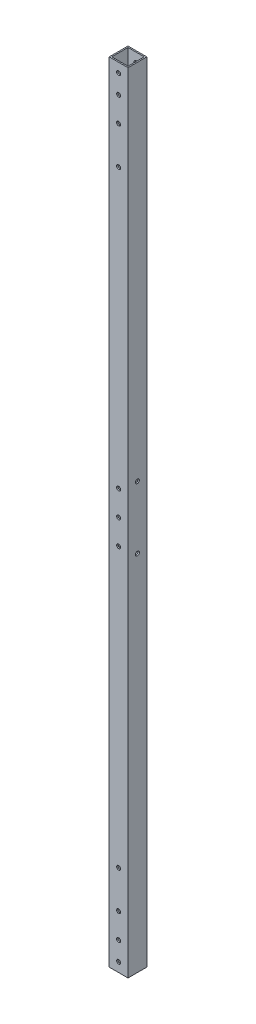
SolidWorks part; units mm, degrees
ref_plane "前视基准面" through (0, 0, 0) normal (0, 0, 1) x (1, 0, 0)
ref_plane "上视基准面" through (0, 0, 0) normal (0, 1, 0) x (1, 0, 0)
ref_plane "右视基准面" through (0, 0, 0) normal (1, 0, 0) x (0, 0, -1)
sketch "草图2" plane through (0, 0, 0) normal (0, 1, 0) x (1, 0, 0)
  line L1 (-7.5, -7.5) -> (7.5, -7.5)
  line L2 (-7.5, -7.5) -> (-7.5, 7.5)
  line L3 (-7.5, 7.5) -> (7.5, 7.5)
  line L4 (7.5, -7.5) -> (7.5, 7.5)
  line L5 (-7.5, -7.5) -> (7.5, 7.5) construction
  line L6 (-7.5, 7.5) -> (7.5, -7.5) construction
  point P0 (0, 0)
  dimension "D1" = 15
  dimension "D2" = 15
extrude "拉伸-薄壁1" add sketch "草图2" along normal blind 630 thin thin type one direction reverse wall 1
sketch "草图3" plane through (0, 0, 7.5) normal (0, 0, 1) x (1, 0, 0)
  line L0 (0, 0) -> (0, 630) construction
  line L1 (-7.5, 630) -> (7.5, 630) construction
  line L2 (-1000, 315) -> (49000, 315) construction
  line L3 (-7.5, 0) -> (7.5, 0) construction
  circle A0 centre (0, 7.5) radius 1.6
  circle A1 centre (0, 22.5) radius 1.6
  circle A2 centre (0, 42.5) radius 1.6
  circle A3 centre (0, 72.5) radius 1.6
  circle A4 centre (0, 315) radius 1.6
  circle A5 centre (0, 295) radius 1.6
  circle A6 centre (0, 335) radius 1.6
  circle A7 centre (0, 557.5) radius 1.6
  circle A8 centre (0, 587.5) radius 1.6
  circle A9 centre (0, 607.5) radius 1.6
  circle A10 centre (0, 622.5) radius 1.6
  point P14 (0, 315)
  dimension "D1" = 3.2
  dimension "D3" = 15
  dimension "D4" = 20
  dimension "D5" = 30
  dimension "D6" = 20
  dimension "D7" = 20
  dimension "D2" = 7.5
extrude "切除-拉伸1" cut sketch "草图3" against normal through all
sketch "草图4" plane through (7.5, 0, 0) normal (1, 0, 0) x (0, 0, -1)
  line L0 (0, 0) -> (0, 630) construction
  line L1 (-7.5, 630) -> (7.5, 630) construction
  circle A0 centre (0, 290) radius 1.6
  circle A1 centre (0, 340) radius 1.6
  point P9 (0, 315)
  dimension "D1" = 3.2
  dimension "D3" = 25
  dimension "D2" = 25
extrude "切除-拉伸2" cut sketch "草图4" against normal through all
